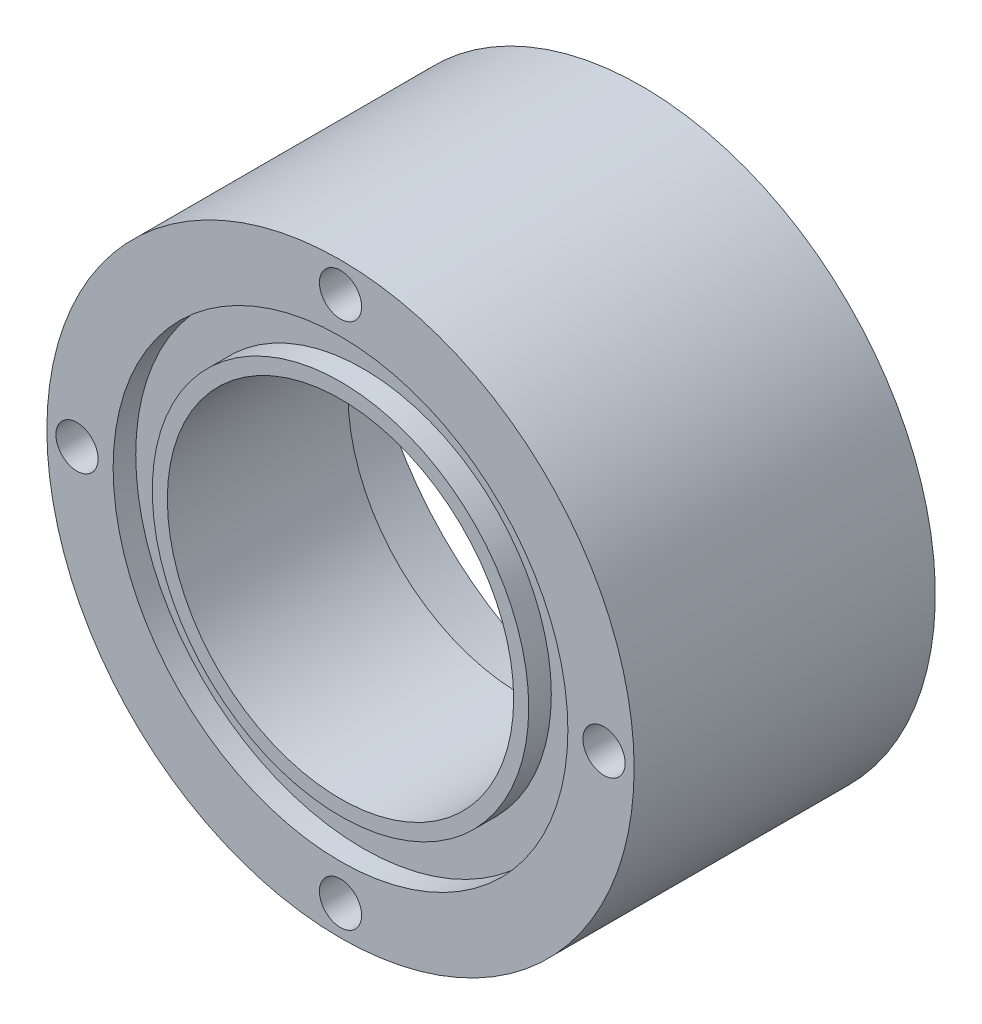
SolidWorks part; units mm, degrees
ref_plane "Front Plane" through (0, 0, 0) normal (0, 0, 1) x (1, 0, 0)
ref_plane "Top Plane" through (0, 0, 0) normal (0, 1, 0) x (1, 0, 0)
ref_plane "Right Plane" through (0, 0, 0) normal (1, 0, 0) x (0, 0, -1)
sketch "Sketch1" plane through (0, 0, 0) normal (0, 0, 1) x (1, 0, 0)
  circle A0 centre (0, 0) radius 11.5
extrude "Extrude-Thin1" add sketch "Sketch1" along normal blind 12 thin
sketch "Sketch2" plane through (0, 0, 12) normal (0, 0, 1) x (1, 0, 0)
  line L0 (0, 0) -> (0, 17.5)
  circle A0 centre (0, 17.5) radius 1.4
  point P4 (0, 16.9907)
extrude "Cut-Extrude1" cut sketch "Sketch2" against normal blind 7
pattern_circular "CirPattern1" count 4 over 360 about axis through (0, 0, 0) along (0, 0, 1) of "Cut-Extrude1"
sketch "Sketch5" plane through (0, 0, 12) normal (0, 0, 1) x (1, 0, 0)
  circle A0 centre (0, 0) radius 12.5
  circle A1 centre (0, 0) radius 15.1
  dimension "D1" = 2.6
extrude "Cut-Extrude3" cut sketch "Sketch5" against normal blind 1.5
sketch "Sketch6" plane through (0, 0, 0) normal (0, 0, -1) x (-1, 0, 0)
  line L2 (0, -17) -> (0, 0) construction
  circle A14 centre (0, -17) radius 1.4
  circle A15 centre (-17, 0) radius 1.4
  circle A16 centre (0, 17) radius 1.4
  circle A17 centre (17, 0) radius 1.4
  point P12 (0, 0)
  dimension "D1" = 4
extrude "Cut-Extrude4" cut sketch "Sketch6" against normal blind 7
sketch "Sketch7" plane through (0, 0, 0) normal (0, 0, -1) x (-1, 0, 0)
  circle A0 centre (0, 0) radius 12.5 construction
  circle A1 centre (0, 0) radius 15.1
  circle A2 centre (0, 0) radius 15.1
  circle A3 centre (0, 0) radius 12.5
  dimension "D1" = 0
extrude "Cut-Extrude5" cut sketch "Sketch7" against normal blind 1.5
sketch "Sketch9" plane through (0, 0, 0) normal (0, 0, -1) x (-1, 0, 0)
  circle A1 centre (0, 0) radius 19.5
  circle A2 centre (0, 0) radius 19.5
  dimension "D1" = 0
extrude "Extrude-Thin3" add sketch "Sketch9" along normal blind 8 thin thin type one direction reverse wall 1
ref_plane "Plane1" through (0, 0, 4) normal (0, 0, 1) x (1, 0, 0)
